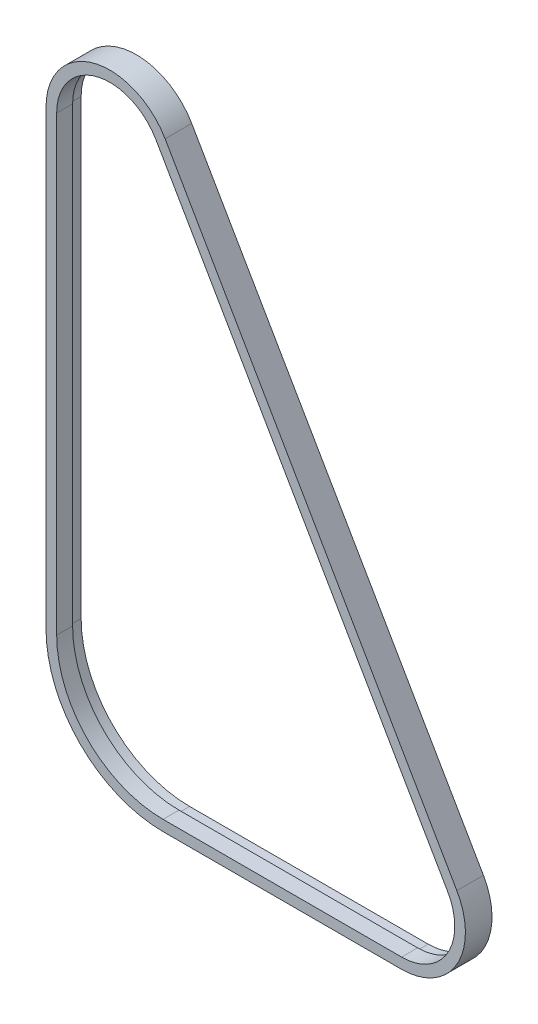
SolidWorks part; units mm, degrees
ref_plane "Front Plane" through (0, 0, 0) normal (0, 0, 1) x (1, 0, 0)
ref_plane "Top Plane" through (0, 0, 0) normal (0, 1, 0) x (1, 0, 0)
ref_plane "Right Plane" through (0, 0, 0) normal (1, 0, 0) x (0, 0, -1)
sketch "Sketch1" plane through (0, 0, 0) normal (0, 0, 1) x (1, 0, 0)
  line L0 (-100, 100) -> (-100, 525)
  line L1 (-6.6987, 550) -> (267.5426, 75)
  line L2 (224.2414, 0) -> (0, 0)
  line L3 (-453.0078, 575) -> (452.8631, 575) construction
  line L4 (1.9615, 555) -> (276.2029, 80)
  line L5 (224.2414, -10) -> (0, -10)
  line L6 (-110, 100) -> (-110, 525)
  arc A0 (-100, 100) -> (0, 0) centre (0, 100) ccw
  arc A1 (-100, 525) -> (-6.6987, 550) centre (-50, 525) cw
  arc A2 (267.5426, 75) -> (224.2414, 0) centre (224.2414, 50) cw
  arc A3 (276.2029, 80) -> (224.2414, -10) centre (224.2414, 50) cw
  arc A4 (-110, 100) -> (0, -10) centre (0, 100) ccw
  arc A5 (-110, 525) -> (1.9615, 555) centre (-50, 525) cw
  dimension "D1" = 100
  dimension "D2" = 50
  dimension "D3" = 575
  dimension "D4" = 60
  dimension "D5" = 10
extrude "Boss-Extrude1" add sketch "Sketch1" along normal blind 25
sketch "Sketch3" plane through (0, 0, 0) normal (0, 0, 1) x (1, 0, 0)
  line L15 (269.2747, 76) -> (-4.9667, 551)
  line L16 (0, -2) -> (224.2414, -2)
  line L17 (-102, 525) -> (-102, 100)
  line L18 (269.2747, 76) -> (-4.9667, 551)
  line L19 (0, -2) -> (224.2414, -2)
  line L20 (-102, 525) -> (-102, 100)
  arc A12 (-4.9667, 551) -> (-102, 525) centre (-50, 525) ccw
  arc A13 (224.2414, -2) -> (269.2747, 76) centre (224.2414, 50) ccw
  arc A14 (-102, 100) -> (0, -2) centre (0, 100) ccw
  arc A15 (-4.9667, 551) -> (-102, 525) centre (-50, 525) ccw
  arc A16 (224.2414, -2) -> (269.2747, 76) centre (224.2414, 50) ccw
  arc A17 (-102, 100) -> (0, -2) centre (0, 100) ccw
  dimension "D1" = 2
extrude "Cut-Extrude2" cut sketch "Sketch3" along normal blind 10
